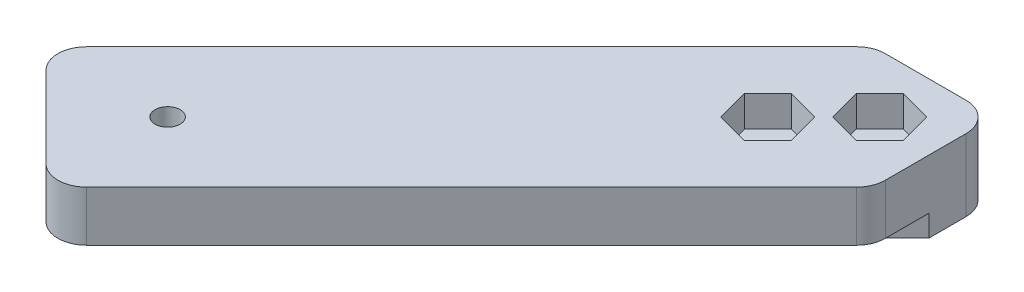
SolidWorks part; units mm, degrees
material "PC High Viscosity"
ref_plane "Front Plane" through (0, 0, 0) normal (0, 0, 1) x (1, 0, 0)
ref_plane "Top Plane" through (0, 0, 0) normal (0, 1, 0) x (1, 0, 0)
ref_plane "Right Plane" through (0, 0, 0) normal (1, 0, 0) x (0, 0, -1)
sketch "Sketch1" plane through (0, 0, 0) normal (0, 1, 0) x (1, 0, 0)
  line L0 (0, 0) -> (49.4975, 49.4975) construction
  line L1 (-16.9, 57.4975) -> (57.4975, 57.4975)
  line L2 (-16.9, 57.4975) -> (-16.9, -18.94)
  line L3 (-16.9, -18.94) -> (57.4975, -18.94)
  line L4 (57.4975, 57.4975) -> (57.4975, -18.94)
  circle A0 centre (0, 0) radius 1.75
  circle A1 centre (49.4975, 49.4975) radius 2
  circle A2 centre (41.7193, 41.7193) radius 2
  point P0 (0, 0)
  point P10 (56.1761, 56.4664)
  point P11 (57.4975, -16.6074)
  dimension "D1" = 3.5
  dimension "D2" = 16.9
  dimension "D5" = 4
  dimension "D6" = 4
  dimension "D3" = 70
  dimension "D4" = 45
  dimension "D7" = 11
  dimension "D8" = 8
  dimension "D9" = 8
  dimension "D10" = 18.94
extrude "Boss-Extrude1" add sketch "Sketch1" along normal blind 7
sketch "Sketch2" plane through (0, 7, 0) normal (0, 1, 0) x (1, 0, 0)
  line L0 (0, 0) -> (49.4975, 49.4975) construction
  line L1 (38.4533, 38.4533) -> (42.9147, 37.2579)
  line L2 (42.9147, 37.2579) -> (46.1807, 40.5239)
  line L3 (46.1807, 40.5239) -> (44.9853, 44.9853)
  line L4 (44.9853, 44.9853) -> (40.5239, 46.1807)
  line L5 (40.5239, 46.1807) -> (37.2579, 42.9147)
  line L6 (37.2579, 42.9147) -> (38.4533, 38.4533)
  line L7 (50.6929, 45.0361) -> (53.9589, 48.302)
  line L8 (53.9589, 48.302) -> (52.7635, 52.7635)
  line L9 (52.7635, 52.7635) -> (48.302, 53.9589)
  line L10 (48.302, 53.9589) -> (45.0361, 50.6929)
  line L11 (45.0361, 50.6929) -> (46.2315, 46.2315)
  line L12 (46.2315, 46.2315) -> (50.6929, 45.0361)
  circle A0 centre (41.7193, 41.7193) radius 4 construction
  circle A1 centre (49.4975, 49.4975) radius 4 construction
  point P19 (44.9565, 44.9565)
  point P21 (34.4348, 34.4348)
  dimension "D1" = 8
extrude "Cut-Extrude1" cut sketch "Sketch2" against normal blind 4.3
sketch "Sketch3" plane through (0, 7, 0) normal (0, 1, 0) x (1, 0, 0)
  line L0 (-16.9, 0) -> (2.04, -18.94)
  line L1 (-16.9, 57.4975) -> (-16.9, -18.94) construction
  line L2 (-16.9, -18.94) -> (57.4975, -18.94) construction
  line L3 (-16.9, 0) -> (-16.9, -18.94)
  line L4 (-16.9, -18.94) -> (2.04, -18.94)
  dimension "D1" = 18.94
  dimension "D2" = 45
extrude "Cut-Extrude2" cut sketch "Sketch3" against normal through all
sketch "Sketch4" plane through (0, 0, 0) normal (0, -1, 0) x (1, 0, 0)
  line L1 (1.7321, -3) -> (3.4641, 0)
  line L2 (3.4641, 0) -> (1.7321, 3)
  line L3 (1.7321, 3) -> (-1.7321, 3)
  line L4 (-1.7321, 3) -> (-3.4641, 0)
  line L5 (-3.4641, 0) -> (-1.7321, -3)
  line L6 (-1.7321, -3) -> (1.7321, -3)
  circle A0 centre (0, 0) radius 3 construction
  point P1 (2.5399, 4)
  dimension "D1" = 6
extrude "Cut-Extrude3" cut sketch "Sketch4" against normal blind 3.2
sketch "Sketch5" plane through (0, 0, 0) normal (0, -1, 0) x (1, 0, 0)
  line L0 (48.3051, -57.4975) -> (57.4975, -57.4975)
  line L1 (57.4975, -57.4975) -> (-16.9, -57.4975) construction
  line L2 (57.4975, -57.4975) -> (57.4975, -48.3051)
  line L3 (57.4975, 18.94) -> (57.4975, -57.4975) construction
  line L4 (57.4975, -48.3051) -> (40.6586, -31.4663)
  line L5 (40.6586, -31.4663) -> (31.4663, -40.6586)
  line L6 (31.4663, -40.6586) -> (48.3051, -57.4975)
  line L7 (49.4975, -49.4975) -> (36.0624, -36.0624) construction
  line L8 (0, 0) -> (36.0624, -36.0624) construction
  circle A0 centre (41.7193, -41.7193) radius 2 construction
  circle A1 centre (41.7193, -41.7193) radius 2
  circle A2 centre (49.4975, -49.4975) radius 2 construction
  circle A3 centre (49.4975, -49.4975) radius 2
  point P9 (40.552, -23.2361)
  point P15 (57.4975, -43.7644)
  point P16 (39.1397, -26.6155)
  dimension "D1" = 13
  dimension "D2" = 8
extrude "Boss-Extrude2" add sketch "Sketch5" along normal blind 3
sketch "Sketch6" plane through (0, 7, 0) normal (0, 1, 0) x (1, 0, 0)
  line L0 (-16.9, 0) -> (40.5975, 57.4975)
  line L1 (57.4975, 57.4975) -> (-16.9, 57.4975) construction
  line L3 (57.4975, -18.94) -> (57.4975, 57.4975) construction
  line L4 (57.4975, 40.5975) -> (57.4975, -18.94)
  line L5 (57.4975, -18.94) -> (2.04, -18.94)
  line L6 (-16.9, 0) -> (-16.9, 57.4975)
  line L7 (-16.9, 57.4975) -> (40.5975, 57.4975)
  line L8 (2.04, -18.94) -> (-16.9, 0) construction
  line L9 (40.5975, 57.4975) -> (57.4975, 40.5975) construction
  line L10 (0, -16.9) -> (57.4975, 40.5975)
  line L11 (2.04, -18.94) -> (0, -16.9)
extrude "Cut-Extrude4" cut sketch "Sketch6" against normal through all
fillet "Fillet1" radius 4 5 edges at (57.4975, 2, -57.4975) (40.5975, 3.5, -57.4975) (57.4975, 3.5, -40.5975) (-16.9, 3.5, 0) (0, 3.5, 16.9)
